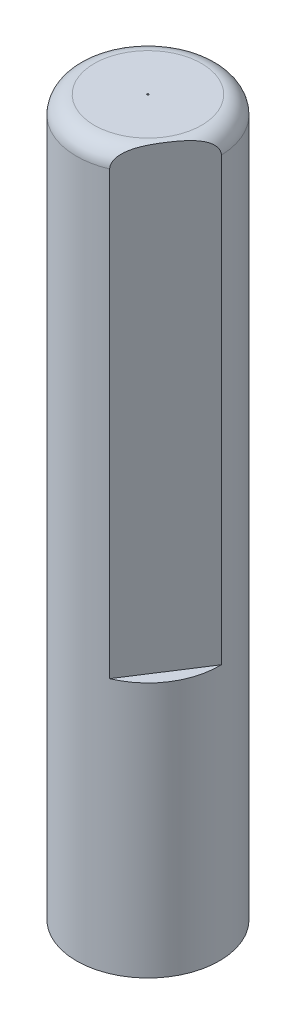
SolidWorks part; units mm, degrees
ref_plane "Front Plane" through (0, 0, 0) normal (0, 0, 1) x (1, 0, 0)
ref_plane "Top Plane" through (0, 0, 0) normal (0, 1, 0) x (1, 0, 0)
ref_plane "Right Plane" through (0, 0, 0) normal (1, 0, 0) x (0, 0, -1)
sketch "Sketch1" plane through (0, 0, 0) normal (0, 1, 0) x (1, 0, 0)
  circle A0 centre (0, 0) radius 4
  dimension "D1" = 8
extrude "Boss-Extrude1" add sketch "Sketch1" along normal blind 40 contours A0
fillet "Fillet1" radius 1 1 edges at (0, 40, 4)
sketch "Sketch2" plane through (0, 40, 0) normal (0, 1, 0) x (1, 0, 0)
  line L0 (1.5462, -3.6891) -> (3.9985, 0.1091)
  circle A0 centre (0, 0) radius 4 construction
  arc A1 (1.5462, -3.6891) -> (3.9985, 0.1091) centre (0, 0) ccw
  dimension "D1" = 3.3
extrude "Cut-Extrude1" cut sketch "Sketch2" against normal blind 25.7
sketch "Sketch3" plane through (0, 40, 0) normal (0, 1, 0) x (1, 0, 0)
  circle A0 centre (0, 0) radius 0.05
  dimension "D1" = 0.1
extrude "Cut-Extrude2" cut sketch "Sketch3" against normal blind 0.1
